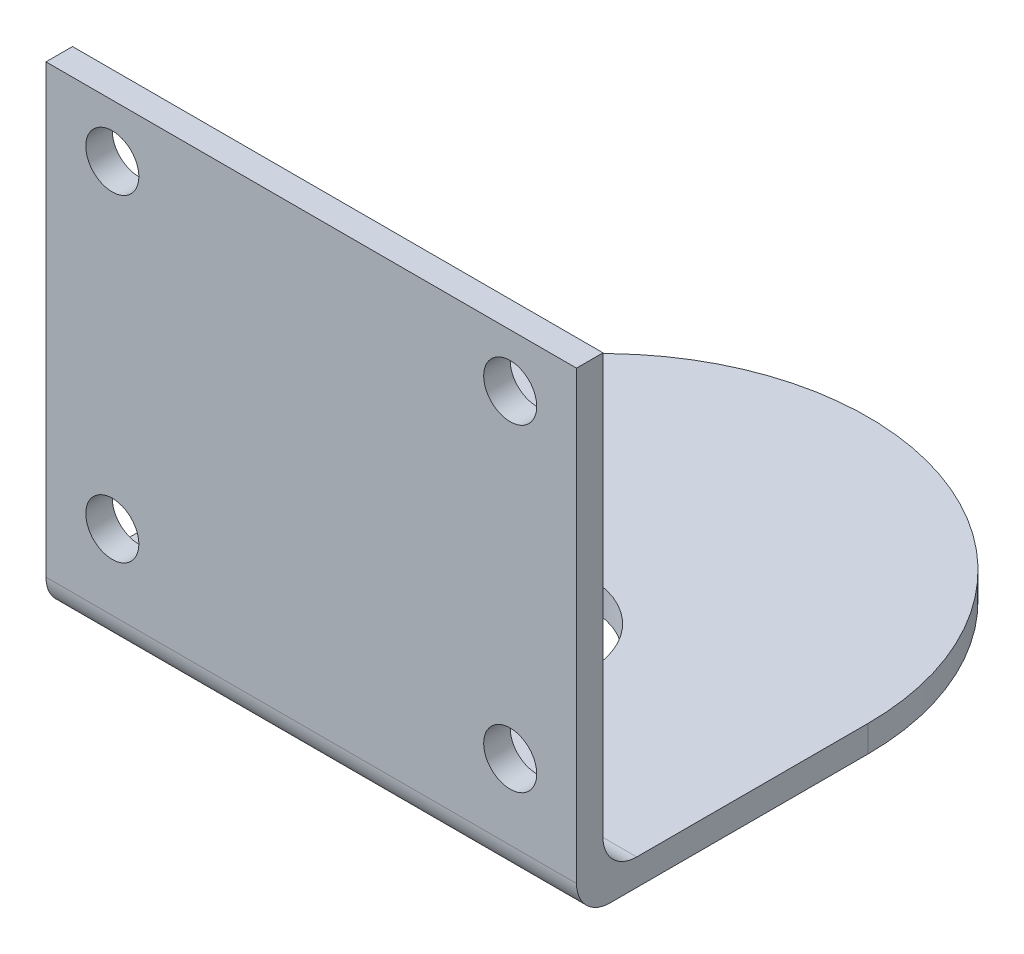
SolidWorks part; units mm, degrees
ref_plane "Front Plane" through (0, 0, 0) normal (0, 0, 1) x (1, 0, 0)
ref_plane "Top Plane" through (0, 0, 0) normal (0, 1, 0) x (1, 0, 0)
ref_plane "Right Plane" through (0, 0, 0) normal (1, 0, 0) x (0, 0, -1)
sketch "Sketch1" plane through (0, 0, 0) normal (0, 0, 1) x (1, 0, 0)
  line L1 (-20.0025, -18.0975) -> (20.0025, -18.0975)
  line L2 (-20.0025, -18.0975) -> (-20.0025, 18.0975)
  line L3 (-20.0025, 18.0975) -> (20.0025, 18.0975)
  line L4 (20.0025, -18.0975) -> (20.0025, 18.0975)
  line L5 (-20.0025, -18.0975) -> (20.0025, 18.0975) construction
  line L6 (-20.0025, 18.0975) -> (20.0025, -18.0975) construction
  point P0 (0, 0)
  dimension "D1" = 40.005
  dimension "D2" = 36.195
extrude "Boss-Extrude1" add sketch "Sketch1" along normal blind 2 contours L4 L3 L2 L1
sketch "Sketch3" plane through (0, -18.0975, 0) normal (0, -1, 0) x (1, 0, 0)
  line L0 (-20.0025, 2) -> (-20.0025, 0) construction
  line L1 (20.0025, 0) -> (-20.0025, 0)
  line L2 (20.0025, 0) -> (20.0025, -19.9975)
  line L4 (-20.0025, 0) -> (-20.0025, -19.9975)
  line L5 (0, -19.9072) -> (0, 19.9072) construction
  arc A0 (0.4472, 0) -> (-0.4472, 0) centre (0, -19.9975) ccw
  arc A1 (-20.0025, -19.9975) -> (20.0025, -19.9975) centre (0, -19.9975) ccw
  point P1 (0, 0)
  point P9 (0, 0)
extrude "Boss-Extrude3" add sketch "Sketch3" against normal blind 2 contours A1 L2 L1 L4
fillet "Fillet1" radius 2.54 2 edges at (0, -16.0975, 0) (0, -18.0975, 2)
sketch "Sketch4" plane through (0, 0, 0) normal (0, 0, -1) x (-1, 0, 0)
  line L0 (-20.0025, -13.5575) -> (-20.0025, 18.0975) construction
  line L1 (20.0025, -13.5575) -> (20.0025, 18.0975) construction
  line L2 (20.0025, 18.0975) -> (-20.0025, 18.0975) construction
  circle A0 centre (-15.0025, 14.0975) radius 2
  circle A1 centre (15.0025, 14.0975) radius 2
  circle A2 centre (15.0025, -9.9025) radius 2
  circle A3 centre (-15.0025, -9.9025) radius 2
  point P8 (-16.3175, 14.7886)
  dimension "D1" = 4
  dimension "D2" = 5
  dimension "D3" = 5
  dimension "D4" = 5
  dimension "D5" = 5
  dimension "D6" = 4
  dimension "D7" = 4
  dimension "D8" = 24
  dimension "D9" = 24
extrude "Cut-Extrude1" cut sketch "Sketch4" against normal through all
sketch "Sketch5" plane through (0, -18.0975, 0) normal (0, -1, 0) x (1, 0, 0)
  line L0 (-20.0025, 2) -> (20.0025, 2) construction
  line L1 (0, -19.9072) -> (0, 19.9072) construction
  circle A0 centre (0, -13) radius 6
  point P4 (0, 0)
  dimension "D1" = 12
  dimension "D2" = 15
extrude "Cut-Extrude2" cut sketch "Sketch5" against normal through all and the other way through all contours A0
